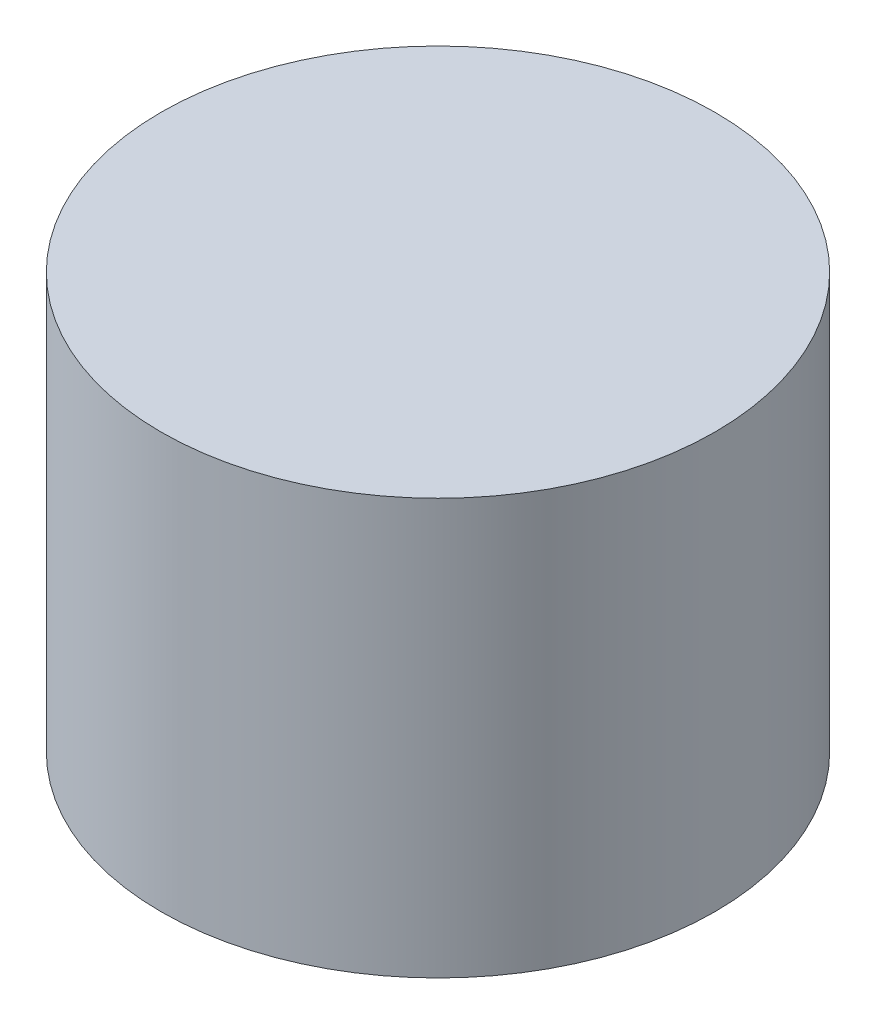
SolidWorks part; units mm, degrees
material "Cast Alloy Steel"
ref_plane "Front Plane" through (0, 0, 0) normal (0, 0, 1) x (1, 0, 0)
ref_plane "Top Plane" through (0, 0, 0) normal (0, 1, 0) x (1, 0, 0)
ref_plane "Right Plane" through (0, 0, 0) normal (1, 0, 0) x (0, 0, -1)
sketch "Sketch1" plane through (0, 0, 0) normal (0, 1, 0) x (1, 0, 0)
  circle A0 centre (0, 0) radius 10
  dimension "D1" = 20
extrude "Boss-Extrude1" add sketch "Sketch1" along normal mid plane 15 contours A0
sketch "Sketch2" plane through (0, -7.5, 0) normal (0, -1, 0) x (1, 0, 0)
  circle A0 centre (0, 0) radius 2
  dimension "D1" = 4
extrude "Cut-Extrude1" cut sketch "Sketch2" against normal blind 10
